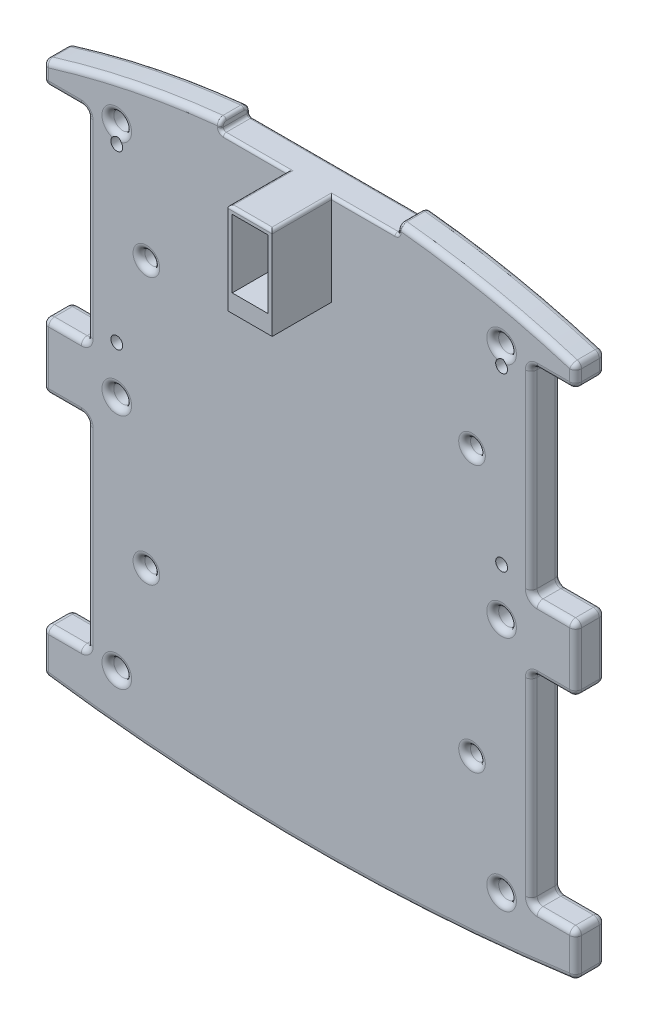
SolidWorks part; units mm, degrees
ref_plane "Front Plane" through (0, 0, 0) normal (0, 0, 1) x (1, 0, 0)
ref_plane "Top Plane" through (0, 0, 0) normal (0, 1, 0) x (1, 0, 0)
ref_plane "Right Plane" through (0, 0, 0) normal (1, 0, 0) x (0, 0, -1)
sketch "Sketch2" plane through (0, 0, 0) normal (0, 0, 1) x (1, 0, 0)
  line L1 (90, 86.2696) -> (-90, 86.2696)
  line L2 (90, 86.2696) -> (90, -93.7304)
  line L3 (90, -93.7304) -> (-90, -93.7304)
  line L4 (-90, 86.2696) -> (-90, -93.7304)
  arc A0 (-90, 86.2696) -> (90, 86.2696) centre (0, -201.8302) cw
  arc A1 (90, -93.7304) -> (-90, -93.7304) centre (0, 549.1136) cw
  point P5 (0, 86.2696)
  point P7 (0, 100)
  point P9 (0, -100)
  dimension "D1" = 180
  dimension "D2" = 180
  dimension "D3" = 0
  dimension "D4" = 100
  dimension "D5" = 100
extrude "Boss-Extrude1" add sketch "Sketch2" along normal blind 10 contours L1 L4 L3 L2 | A0 L1 | A1 L3
sketch "Sketch3" plane through (0, 0, 0) normal (0, 0, 1) x (1, 0, 0)
  line L0 (90, 86.2696) -> (90, -93.7304) construction
  line L1 (90, 79) -> (75, 79)
  line L2 (90, 79) -> (90, 11)
  line L3 (90, 11) -> (75, 11)
  line L4 (75, 79) -> (75, 11)
  point P6 (90, 45)
  dimension "D1" = 68
  dimension "D2" = 15
  dimension "D3" = 45
extrude "Cut-Extrude2" cut sketch "Sketch3" along normal blind 10
pattern_linear "LPattern1" count 2 spacing 165 along (-1, 0, 0) count 2 spacing 90 along (0, -1, 0) of "Cut-Extrude2"
sketch "Sketch4" plane through (0, 0, 0) normal (0, 0, 1) x (1, 0, 0)
  circle A0 centre (-65, 0) radius 3
  dimension "D1" = 0
  dimension "D2" = 65
extrude "Cut-Extrude4" cut sketch "Sketch4" along normal blind 10
pattern_linear "LPattern2" count 2 spacing 80 along (0, 1, 0) count 2 spacing 130 along (1, 0, 0) of "Cut-Extrude4"
pattern_linear "LPattern3" count 2 spacing 80 along (0, -1, 0) of "LPattern2", "Cut-Extrude4"
sketch "Sketch5" plane through (0, 0, 0) normal (0, 0, 1) x (1, 0, 0)
  line L0 (-75, 11) -> (-75, 79) construction
  circle A0 centre (-55, 44.9865) radius 2.5
  dimension "D1" = 20
extrude "Cut-Extrude5" cut sketch "Sketch5" along normal blind 10
pattern_linear "LPattern4" count 2 spacing 90 along (0, -1, 0) count 2 spacing 110 along (1, 0, 0) of "Cut-Extrude5"
fillet "Fillet1" radius 2 80 edges at (0, 100, 10) (-62, -80, 0) (-62, -80, 10) (-52.5, 44.9865, 0) (-52.5, 44.9865, 10) (-52.5, -45.0135, 10) (-52.5, -45.0135, 0) (57.5, 44.9865, 10) (57.5, 44.9865, 0) (57.5, -45.0135, 10) (57.5, -45.0135, 0) (-90, 82.6348, 10) (90, 0, 0) (90, 0, 10) (0, -100, 10) (90, 11, 5) (82.5, 79, 0) (90, 79, 5) (75, 45, 0) (75, 79, 5) (82.5, 11, 0) (75, 11, 5) (82.5, 79, 10) (75, 45, 10) (82.5, 11, 10) (-90, 0, 0) (-90, -86.3652, 0) (-90, 0, 10) (-90, -86.3652, 10) (90, -86.3652, 0) (90, -86.3652, 10) (90, -79, 5) (82.5, -11, 0) (90, -11, 5) (75, -45, 0) (90, 82.6348, 10) (75, -11, 5) (82.5, -79, 0) (75, -79, 5) (82.5, -11, 10) (75, -45, 10) (82.5, -79, 10) (-75, 45, 0) (-75, 11, 5) (-82.5, 79, 0) (-75, 79, 5) (-90, 79, 5) (0, -100, 0) (-82.5, 11, 0) (-90, 11, 5) (-75, 45, 10) (-82.5, 79, 10) (-82.5, 11, 10) (-75, -45, 0) (-90, 82.6348, 0) (-75, -79, 5) (-82.5, -11, 0) (-75, -11, 5) (-90, -11, 5) (-82.5, -79, 0) (-90, -79, 5) (-75, -45, 10) (-82.5, -11, 10) (-82.5, -79, 10) (0, 100, 0) (90, 82.6348, 0) (-62, 0, 0) (-62, 0, 10) (-62, 80, 10) (-62, 80, 0) (68, 0, 10) (90, -93.7304, 5) (68, 0, 0) (-90, -93.7304, 5) (68, 80, 10) (-90, 86.2696, 5) (68, 80, 0) (90, 86.2696, 5) (68, -80, 0) (68, -80, 10)
sketch "Sketch10" plane through (0, 0, 0) normal (0, 0, -1) x (-1, 0, 0)
  line L1 (-6, 93) -> (6, 93)
  line L2 (-6, 93) -> (-6, 70)
  line L3 (-6, 70) -> (6, 70)
  line L4 (6, 93) -> (6, 70)
  line L5 (7.5, 99) -> (-7.5, 99)
  line L6 (7.5, 99) -> (7.5, 64)
  line L7 (7.5, 64) -> (-7.5, 64)
  line L8 (-7.5, 99) -> (-7.5, 64)
  arc A0 (88.587, 86.7072) -> (-88.587, 86.7072) centre (0, -201.8302) ccw construction
  point P4 (0, 93)
  point P9 (0, 100)
  point P14 (-6, 81.5)
  point P15 (-7.5, 81.5)
  point P16 (0, 99)
  dimension "D1" = 23
  dimension "D2" = 12
  dimension "D3" = 0
  dimension "D4" = 7
  dimension "D5" = 15
  dimension "D6" = 35
  dimension "D7" = 0
  dimension "D8" = 0
extrude "Boss-Extrude2" add sketch "Sketch10" against normal blind 30
sketch "Sketch13" plane through (0, 0, 10) normal (0, 0, 1) x (1, 0, 0)
  line L1 (-6, 93) -> (6, 93)
  line L2 (-6, 93) -> (-6, 70)
  line L3 (-6, 70) -> (6, 70)
  line L4 (6, 93) -> (6, 70)
extrude "Cut-Extrude6" cut sketch "Sketch13" against normal through all
sketch "Sketch14" plane through (0, 0, 0) normal (0, 0, -1) x (-1, 0, 0)
  line L1 (-7.5, 99) -> (7.5, 99)
  line L2 (-7.5, 99) -> (-7.5, 64)
  line L3 (-7.5, 64) -> (7.5, 64)
  line L4 (7.5, 99) -> (7.5, 64)
  dimension "D1" = 35
  dimension "D2" = 15
sketch "Sketch15" plane through (0, 0, 30) normal (0, 0, 1) x (1, 0, 0)
  line L1 (-7.5, 99) -> (7.5, 99)
  line L2 (-7.5, 99) -> (-7.5, 64)
  line L3 (-7.5, 64) -> (7.5, 64)
  line L4 (7.5, 99) -> (7.5, 64)
sketch "Sketch16" plane through (0, 0, 0) normal (0, 0, -1) x (-1, 0, 0)
  line L1 (30, 100) -> (-30, 100)
  line L2 (30, 100) -> (30, 95)
  line L3 (30, 95) -> (-30, 95)
  line L4 (-30, 100) -> (-30, 95)
  point P4 (0, 100)
  dimension "D1" = 60
  dimension "D2" = 5
  dimension "D3" = 0
extrude "Cut-Extrude8" cut sketch "Sketch16" against normal through all
fillet "Fillet2" radius 1 18 edges at (-30, 98.5054, 5) (30, 98.5054, 5) (-30, 98.0094, 9.3155) (-30, 97.7, 0.399) (30, 98.0094, 0.6845) (30, 97.7, 9.601) (-30, 95.7477, 10) (-30, 95.7477, 0) (30, 95.7477, 0) (30, 95.7477, 10) (-30, 95, 5) (0, 95, 0) (30, 95, 5) (18.75, 95, 10) (7.5, 95, 20) (-7.5, 95, 20) (-18.75, 95, 10) (0, 95, 30)
sketch "Sketch19" plane through (0, 0, 0) normal (0, 0, 1) x (1, 0, 0)
  circle A0 centre (-65, 16) radius 2
  dimension "D1" = 16
  dimension "D2" = 65
extrude "Cut-Extrude11" cut sketch "Sketch19" along normal through all
pattern_linear "LPattern5" count 2 spacing 58 along (0, 1, 0) count 2 spacing 130 along (1, 0, 0) of "Cut-Extrude11"
sketch "Sketch22" plane through (0, 0, 30) normal (0, 0, 1) x (1, 0, 0)
  line L1 (-7.5, 64) -> (7.5, 64)
  line L2 (-7.5, 64) -> (-7.5, 99)
  line L3 (-7.5, 99) -> (7.5, 99)
  line L4 (7.5, 64) -> (7.5, 99)
  line L5 (-6, 70) -> (6, 70)
  line L6 (-6, 70) -> (-6, 93)
  line L7 (-6, 93) -> (6, 93)
  line L8 (6, 70) -> (6, 93)
